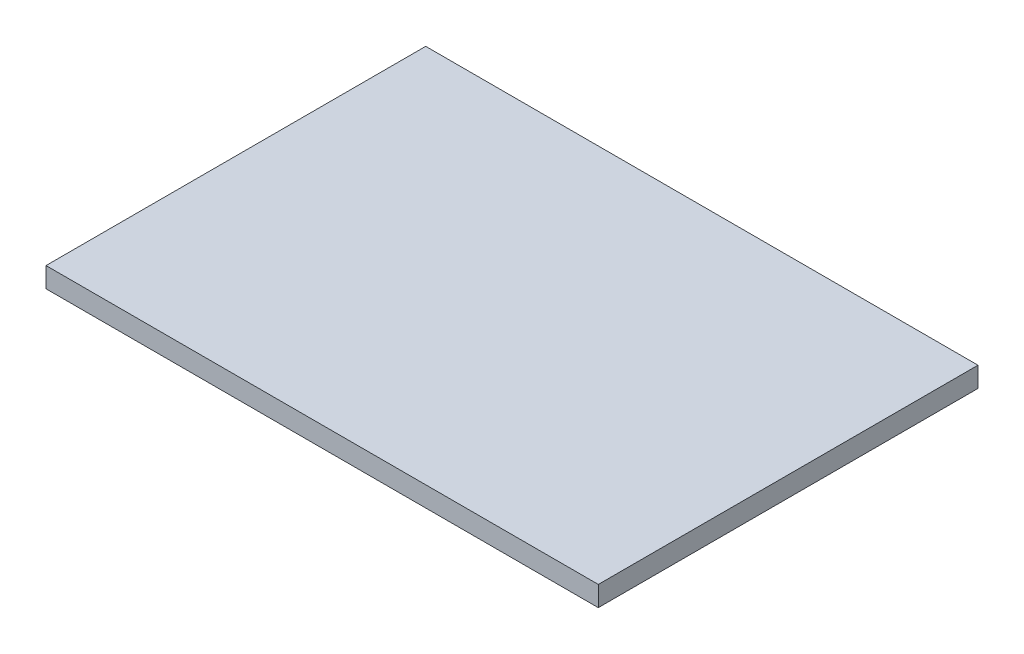
SolidWorks part; units mm, degrees
ref_plane "Спереди" through (0, 0, 0) normal (0, 0, 1) x (1, 0, 0)
ref_plane "Сверху" through (0, 0, 0) normal (0, 1, 0) x (1, 0, 0)
ref_plane "Справа" through (0, 0, 0) normal (1, 0, 0) x (0, 0, -1)
sketch "Эскиз1" plane through (0, 0, 0) normal (0, 1, 0) x (1, 0, 0)
  line L1 (-7214.2857, 2196.4286) -> (2385.7143, 2196.4286)
  line L2 (-7214.2857, 2196.4286) -> (-7214.2857, -4403.5714)
  line L3 (-7214.2857, -4403.5714) -> (2385.7143, -4403.5714)
  line L4 (2385.7143, 2196.4286) -> (2385.7143, -4403.5714)
  dimension "D1" = 6600
  dimension "D2" = 9600
extrude "Бобышка-Вытянуть1" add sketch "Эскиз1" along normal blind 350 contours L2 L1 L4 L3
